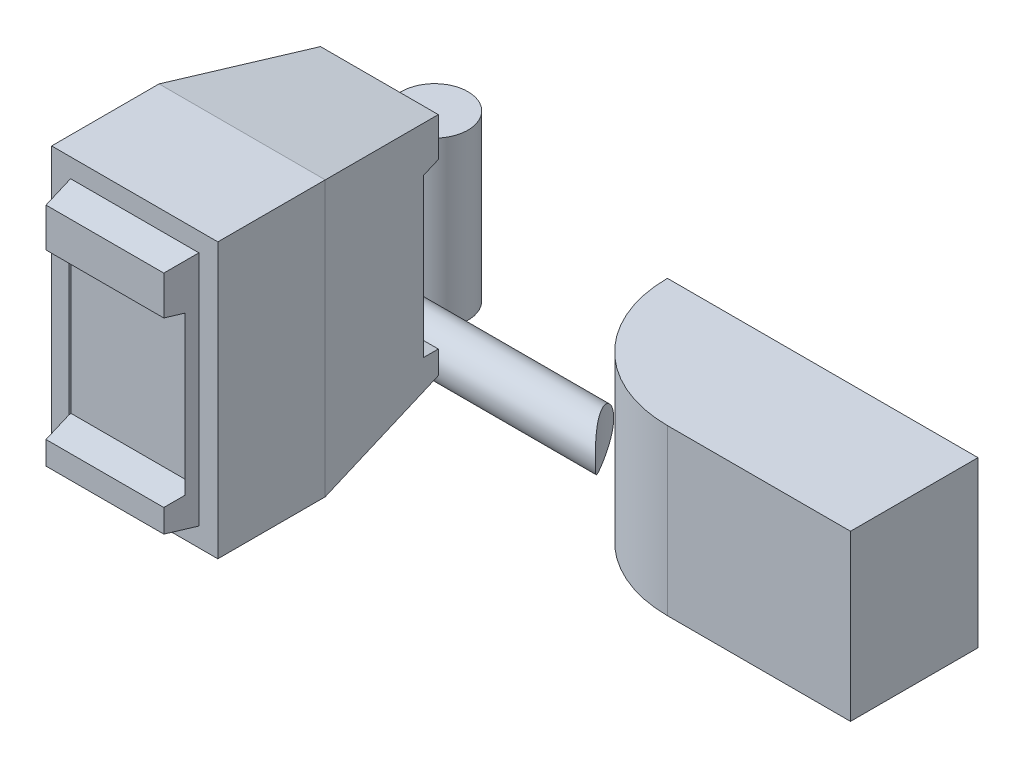
SolidWorks part; units mm, degrees
ref_plane "Front Plane" through (0, 0, 0) normal (0, 0, 1) x (1, 0, 0)
ref_plane "Top Plane" through (0, 0, 0) normal (0, 1, 0) x (1, 0, 0)
ref_plane "Right Plane" through (0, 0, 0) normal (1, 0, 0) x (0, 0, -1)
sketch "Rectangle for cube" plane through (0, 0, 0) normal (0, 1, 0) x (1, 0, 0)
  line L0 (-159.5988, 46.4474) -> (-66.7041, 46.4474)
  line L1 (-66.7041, 46.4474) -> (66.7041, 46.4474)
  line L3 (-66.7041, -46.4474) -> (66.7041, -46.4474)
  line L4 (66.7041, 46.4474) -> (66.7041, -46.4474)
  line L5 (-66.7041, 46.4474) -> (66.7041, -46.4474) construction
  line L6 (-66.7041, -46.4474) -> (66.7041, 46.4474) construction
  arc A0 (-66.7041, -46.4474) -> (-159.5988, 46.4474) centre (-66.7041, 46.4474) cw
  point P0 (0, 0)
extrude "cube" add sketch "Rectangle for cube" along normal blind 40 and the other way blind 80
sketch "Sketch2" plane through (0, 0, 0) normal (0, 1, 0) x (1, 0, 0)
  line L1 (-374.3655, 17.1053) -> (-325.77, 17.1053)
  line L2 (-374.3655, 17.1053) -> (-374.3655, -28.3209)
  line L3 (-374.3655, -28.3209) -> (-325.77, -28.3209)
  line L4 (-325.77, 17.1053) -> (-325.77, -28.3209)
  line L5 (-374.3655, 17.1053) -> (-325.77, -28.3209) construction
  line L6 (-374.3655, -28.3209) -> (-325.77, 17.1053) construction
  circle A0 centre (-350.0677, 67.2855) radius 24.2978
  point P2 (-350.0677, -5.6078)
extrude "Boss-Extrude2" add sketch "Sketch2" along normal up to surface and the other way up to surface separate body up to face at (-28.0335, 40, 4.8098) other way up to face at (-28.0335, -80, 4.8098)
sketch "Sketch3" plane through (-325.77, 0, 0) normal (1, 0, 0) x (0, 0, -1)
  circle A0 centre (-6.4928, -32.1811) radius 17.5272
extrude "Boss-Extrude3" add sketch "Sketch3" along normal offset from surface (162.4571 mm away) 10
sketch "Sketch4" plane through (0, 0, 0) normal (0, 1, 0) x (1, 0, 0)
  line L1 (-307.4621, -176.0752) -> (-186.3694, -176.0752)
  line L2 (-307.4621, -176.0752) -> (-307.4621, -254.3328)
  line L3 (-307.4621, -254.3328) -> (-186.3694, -254.3328)
  line L4 (-186.3694, -176.0752) -> (-186.3694, -254.3328)
  line L5 (-307.4621, -176.0752) -> (-186.3694, -254.3328) construction
  line L6 (-307.4621, -254.3328) -> (-186.3694, -176.0752) construction
  point P0 (-246.9158, -215.204)
extrude "Boss-Extrude4" add sketch "Sketch4" along normal blind 200 separate body
sketch "Sketch5" plane through (0, 0, 176.0752) normal (0, 0, -1) x (-1, 0, 0)
  line L1 (279.4152, 136.3803) -> (217.0574, 136.3803)
  line L2 (279.4152, 136.3803) -> (279.4152, 52.0922)
  line L3 (279.4152, 52.0922) -> (217.0574, 52.0922)
  line L4 (217.0574, 136.3803) -> (217.0574, 52.0922)
  line L5 (279.4152, 136.3803) -> (217.0574, 52.0922) construction
  line L6 (279.4152, 52.0922) -> (217.0574, 136.3803) construction
  point P0 (248.2363, 94.2363)
  line M1 (186.3694, 0) -> (307.4621, 0)
  line M2 (307.4621, 0) -> (307.4621, 200)
  line M3 (307.4621, 200) -> (186.3694, 200)
  line M4 (186.3694, 200) -> (186.3694, 0)
extrude "Boss-Extrude5" add sketch "Sketch5" along normal mid plane 200 draft 10 contours L4 L1 L2 L3 M4 M1 M2 M3
